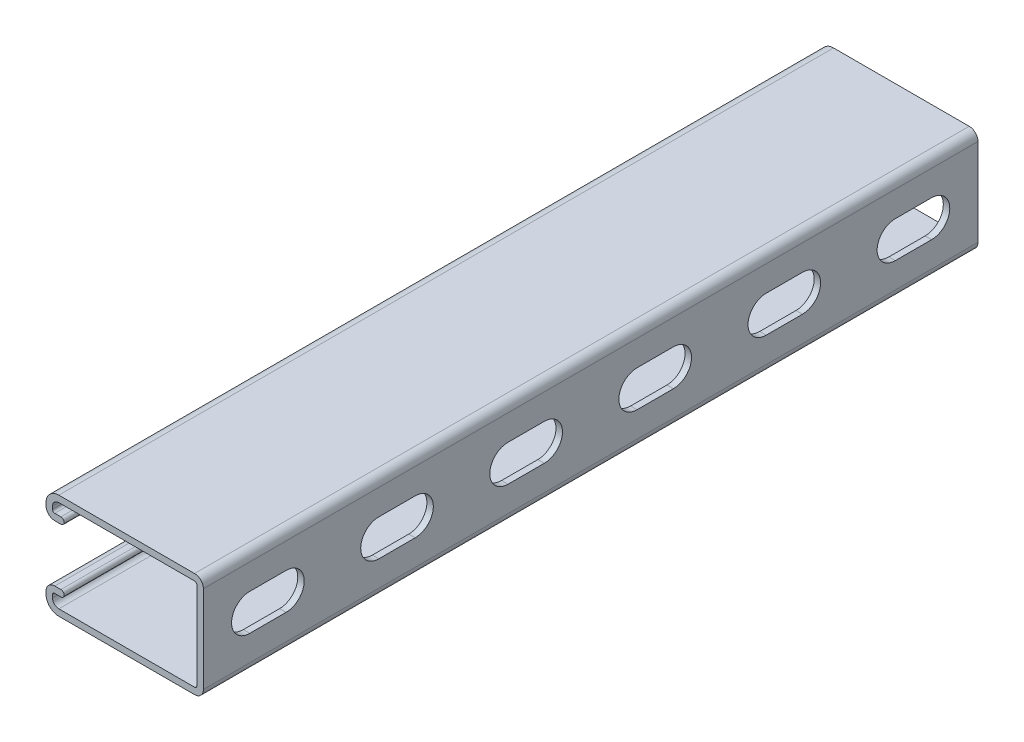
SolidWorks part; units mm, degrees
ref_plane "Front Plane" through (0, 0, 0) normal (0, 0, 1) x (1, 0, 0)
ref_plane "Top Plane" through (0, 0, 0) normal (0, 1, 0) x (1, 0, 0)
ref_plane "Right Plane" through (0, 0, 0) normal (1, 0, 0) x (0, 0, -1)
sketch "Sketch1" plane through (0, 0, 0) normal (0, 0, 1) x (1, 0, 0)
  line L0 (30.9563, 0) -> (-30.9563, 0) construction
  line L3 (-30.9562, 20.6375) -> (30.9562, 20.6375) construction
  line L4 (-30.9562, 20.6375) -> (-30.9562, -20.6375) construction
  line L5 (-30.9562, -20.6375) -> (30.9562, -20.6375) construction
  line L6 (30.9562, 20.6375) -> (30.9562, -20.6375) construction
  line L7 (-25.908, 20.6375) -> (27.4955, 20.6375)
  line L8 (30.9563, 17.1767) -> (30.9563, -17.1767)
  line L9 (28.4163, -17.1767) -> (28.4163, 17.1767)
  line L10 (27.4955, 18.0975) -> (-25.908, 18.0975)
  line L11 (-30.9563, 15.5892) -> (-30.9563, 14.5732)
  line L12 (-27.4955, 11.1125) -> (-25.0889, 11.1125)
  line L14 (-25.0889, 13.6525) -> (-27.4955, 13.6525)
  line L15 (-28.4163, 14.5732) -> (-28.4163, 15.5892)
  line L16 (-28.4162, -14.5732) -> (-28.4162, -15.5892)
  line L17 (-25.0889, -13.6525) -> (-27.4955, -13.6525)
  line L18 (-27.4955, -11.1125) -> (-25.0889, -11.1125)
  line L19 (-30.9563, -15.5892) -> (-30.9563, -14.5732)
  line L20 (27.4955, -18.0975) -> (-25.908, -18.0975)
  line L21 (-25.908, -20.6375) -> (27.4955, -20.6375)
  line L22 (28.4163, -20.6375) -> (28.4163, 20.6375) construction
  arc A1 (30.9563, 17.1767) -> (27.4955, 20.6375) centre (27.4955, 17.1767) ccw
  arc A2 (28.4163, 17.1767) -> (27.4955, 18.0975) centre (27.4955, 17.1767) ccw
  arc A4 (-25.908, 20.6375) -> (-30.9563, 15.5892) centre (-25.908, 15.5892) ccw
  arc A5 (-30.9563, 14.5732) -> (-27.4955, 11.1125) centre (-27.4955, 14.5732) ccw
  arc A6 (-25.0889, 11.1125) -> (-25.0889, 13.6525) centre (-25.0889, 12.3825) ccw
  arc A7 (-27.4955, 13.6525) -> (-28.4163, 14.5732) centre (-27.4955, 14.5732) cw
  arc A8 (-28.4163, 15.5892) -> (-25.908, 18.0975) centre (-25.908, 15.5892) cw
  arc A9 (-28.4162, -15.5892) -> (-25.908, -18.0975) centre (-25.908, -15.5892) ccw
  arc A10 (-27.4955, -13.6525) -> (-28.4162, -14.5732) centre (-27.4955, -14.5732) ccw
  arc A11 (-25.0889, -11.1125) -> (-25.0889, -13.6525) centre (-25.0889, -12.3825) cw
  arc A12 (-30.9563, -14.5732) -> (-27.4955, -11.1125) centre (-27.4955, -14.5732) cw
  arc A13 (-25.908, -20.6375) -> (-30.9563, -15.5892) centre (-25.908, -15.5892) cw
  arc A14 (28.4163, -17.1767) -> (27.4955, -18.0975) centre (27.4955, -17.1767) cw
  arc A15 (30.9563, -17.1767) -> (27.4955, -20.6375) centre (27.4955, -17.1767) cw
  point P24 (30.9562, 20.6375)
  point P65 (28.4163, 0)
  dimension "D1" = 3.4608
  dimension "D2" = 5.0482
  dimension "D3" = 3.4608
  dimension "Channel Height" = 61.9125
  dimension "Channel Width" = 41.275
  dimension "D5" = 7.1374
  dimension "Thickness" = 2.54
  dimension "Inside Channel Width" = 22.225
sketch "Sketch3" plane through (0, 0, 0) normal (1, 0, 0) x (0, 0, -1)
  line L0 (-152.4, 0) -> (152.4, 0) construction
  line L1 (-134.1438, 0) -> (-119.8562, 0) construction
  line L2 (-134.1438, 7.1438) -> (-119.8562, 7.1438)
  line L3 (-134.1438, -7.1438) -> (-119.8562, -7.1438)
  line L4 (-127, 0) -> (-76.2, 0) construction
  line L5 (-141.2875, 0) -> (-90.4875, 0) construction
  arc A0 (-134.1438, 7.1438) -> (-134.1438, -7.1438) centre (-134.1438, 0) ccw
  arc A1 (-119.8562, -7.1438) -> (-119.8562, 7.1438) centre (-119.8562, 0) ccw
  point P2 (-25.4, 0)
  point P3 (25.4, 0)
  point P5 (57.15, 0)
  point P6 (-127, 0)
  point P13 (-141.2875, 0)
  point P14 (-76.2, 0)
  point P15 (-112.7125, 0)
  point P16 (-90.4875, 0)
  dimension "D1" = 127
  dimension "D2" = 127
  dimension "Length" = 304.8
  dimension "Slot End-to-Channel End" = 11.1125
  dimension "Slot Width" = 14.2875
  dimension "Slot Length" = 28.575
  dimension "Slot Center-to-Center" = 50.8
  dimension "Slot Center-to-Channel End" = 25.4
  dimension "Slot End-to-End" = 22.225
  dimension "D3" = 95.25
sketch "Sketch5" plane through (0, 0, 0) normal (0, 0, 1) x (1, 0, 0)
  line L14 (-25.908, -20.6375) -> (27.4955, -20.6375)
  line L15 (-30.9563, -14.5732) -> (-30.9563, -15.5892)
  line L16 (-25.0889, -11.1125) -> (-27.4955, -11.1125)
  line L17 (-27.4955, -13.6525) -> (-25.0889, -13.6525)
  line L18 (-28.4162, -15.5892) -> (-28.4162, -14.5732)
  line L19 (27.4955, -18.0975) -> (-25.908, -18.0975)
  line L20 (28.4163, 17.1767) -> (28.4163, -17.1767)
  line L21 (-25.908, 18.0975) -> (27.4955, 18.0975)
  line L22 (-28.4163, 14.5732) -> (-28.4163, 15.5892)
  line L23 (-25.0889, 13.6525) -> (-27.4955, 13.6525)
  line L24 (-27.4955, 11.1125) -> (-25.0889, 11.1125)
  line L25 (-30.9563, 15.5892) -> (-30.9563, 14.5732)
  line L26 (27.4955, 20.6375) -> (-25.908, 20.6375)
  line L27 (30.9563, -17.1767) -> (30.9563, 17.1767)
  line L28 (-25.908, -20.6375) -> (27.4955, -20.6375)
  line L29 (-30.9563, -14.5732) -> (-30.9563, -15.5892)
  line L30 (-25.0889, -11.1125) -> (-27.4955, -11.1125)
  line L31 (-27.4955, -13.6525) -> (-25.0889, -13.6525)
  line L32 (-28.4162, -15.5892) -> (-28.4162, -14.5732)
  line L33 (27.4955, -18.0975) -> (-25.908, -18.0975)
  line L34 (28.4163, 17.1767) -> (28.4163, -17.1767)
  line L35 (-25.908, 18.0975) -> (27.4955, 18.0975)
  line L36 (-28.4163, 14.5732) -> (-28.4163, 15.5892)
  line L37 (-25.0889, 13.6525) -> (-27.4955, 13.6525)
  line L38 (-27.4955, 11.1125) -> (-25.0889, 11.1125)
  line L39 (-30.9563, 15.5892) -> (-30.9563, 14.5732)
  line L40 (27.4955, 20.6375) -> (-25.908, 20.6375)
  line L41 (30.9563, -17.1767) -> (30.9563, 17.1767)
  arc A14 (-30.9563, -15.5892) -> (-25.908, -20.6375) centre (-25.908, -15.5892) ccw
  arc A15 (-27.4955, -11.1125) -> (-30.9563, -14.5732) centre (-27.4955, -14.5732) ccw
  arc A16 (-25.0889, -13.6525) -> (-25.0889, -11.1125) centre (-25.0889, -12.3825) ccw
  arc A17 (-27.4955, -13.6525) -> (-28.4162, -14.5732) centre (-27.4955, -14.5732) ccw
  arc A18 (-28.4162, -15.5892) -> (-25.908, -18.0975) centre (-25.908, -15.5892) ccw
  arc A19 (27.4955, -18.0975) -> (28.4163, -17.1767) centre (27.4955, -17.1767) ccw
  arc A20 (28.4163, 17.1767) -> (27.4955, 18.0975) centre (27.4955, 17.1767) ccw
  arc A21 (-25.908, 18.0975) -> (-28.4163, 15.5892) centre (-25.908, 15.5892) ccw
  arc A22 (-28.4163, 14.5732) -> (-27.4955, 13.6525) centre (-27.4955, 14.5732) ccw
  arc A23 (-25.0889, 11.1125) -> (-25.0889, 13.6525) centre (-25.0889, 12.3825) ccw
  arc A24 (-30.9563, 14.5732) -> (-27.4955, 11.1125) centre (-27.4955, 14.5732) ccw
  arc A25 (-25.908, 20.6375) -> (-30.9563, 15.5892) centre (-25.908, 15.5892) ccw
  arc A26 (30.9563, 17.1767) -> (27.4955, 20.6375) centre (27.4955, 17.1767) ccw
  arc A27 (27.4955, -20.6375) -> (30.9563, -17.1767) centre (27.4955, -17.1767) ccw
  arc A28 (-30.9563, -15.5892) -> (-25.908, -20.6375) centre (-25.908, -15.5892) ccw
  arc A29 (-27.4955, -11.1125) -> (-30.9563, -14.5732) centre (-27.4955, -14.5732) ccw
  arc A30 (-25.0889, -13.6525) -> (-25.0889, -11.1125) centre (-25.0889, -12.3825) ccw
  arc A31 (-27.4955, -13.6525) -> (-28.4162, -14.5732) centre (-27.4955, -14.5732) ccw
  arc A32 (-28.4162, -15.5892) -> (-25.908, -18.0975) centre (-25.908, -15.5892) ccw
  arc A33 (27.4955, -18.0975) -> (28.4163, -17.1767) centre (27.4955, -17.1767) ccw
  arc A34 (28.4163, 17.1767) -> (27.4955, 18.0975) centre (27.4955, 17.1767) ccw
  arc A35 (-25.908, 18.0975) -> (-28.4163, 15.5892) centre (-25.908, 15.5892) ccw
  arc A36 (-28.4163, 14.5732) -> (-27.4955, 13.6525) centre (-27.4955, 14.5732) ccw
  arc A37 (-25.0889, 11.1125) -> (-25.0889, 13.6525) centre (-25.0889, 12.3825) ccw
  arc A38 (-30.9563, 14.5732) -> (-27.4955, 11.1125) centre (-27.4955, 14.5732) ccw
  arc A39 (-25.908, 20.6375) -> (-30.9563, 15.5892) centre (-25.908, 15.5892) ccw
  arc A40 (30.9563, 17.1767) -> (27.4955, 20.6375) centre (27.4955, 17.1767) ccw
  arc A41 (27.4955, -20.6375) -> (30.9563, -17.1767) centre (27.4955, -17.1767) ccw
  dimension "D1" = 0
extrude "Boss-Extrude1" add sketch "Sketch5" along normal up to vertex (152.4 mm away) and the other way up to vertex (152.4 mm away) up to point (0, 0, 152.4) other way up to point (0, 0, -152.4)
sketch "Sketch2" plane through (0, 0, 0) normal (1, 0, 0) x (0, 0, -1)
  line L0 (-134.1438, 0) -> (-119.8562, 0) construction
  line L1 (-134.1438, 7.1438) -> (-119.8562, 7.1438)
  line L2 (-134.1438, -7.1438) -> (-119.8562, -7.1438)
  arc A0 (-134.1438, 7.1438) -> (-134.1438, -7.1438) centre (-134.1438, 0) ccw
  arc A1 (-119.8562, -7.1438) -> (-119.8562, 7.1438) centre (-119.8562, 0) ccw
  point P3 (-127, 0)
extrude "Cut-Extrude1" cut sketch "Sketch2" along normal through all
pattern_linear "LPattern1" count 6 spacing 50.8 along (0, 0, -1) of "Cut-Extrude1"
equation "\"D1@LPattern1\"=\"Slot Center-to-Center@Sketch3\""
equation "\"Hole Count@LPattern1\"=\"Length@Sketch3\" / \"D1@LPattern1\""
equation "\"D1@Sketch3\"=\"Slot Center-to-Center@Sketch3\"*2.5"
equation "\"D2@Sketch3\"=\"D1@Sketch3\""
equation "\"D3@Sketch3\"=\"D1@Sketch3\"*0.75"
